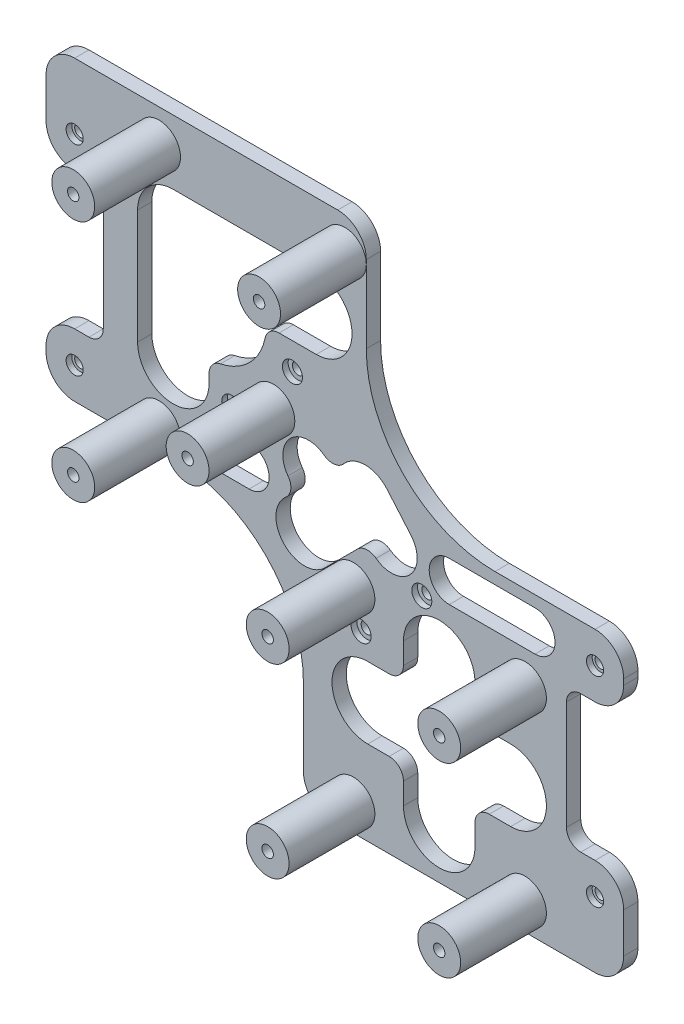
SolidWorks part; units mm, degrees
ref_plane "Přední rovina" through (0, 0, 0) normal (0, 0, 1) x (1, 0, 0)
ref_plane "Horní rovina" through (0, 0, 0) normal (0, 1, 0) x (1, 0, 0)
ref_plane "Pravá rovina" through (0, 0, 0) normal (1, 0, 0) x (0, 0, -1)
sketch "Skica1" plane through (0, 0, 0) normal (0, 0, 1) x (1, 0, 0)
  line L0 (0, 0) -> (101, 0) construction
  line L1 (0, 0) -> (0, 101) construction
  line L2 (-101, 101) -> (101, 101)
  line L3 (101, 101) -> (101, -101)
  line L4 (-101, 101) -> (-101, -101)
  line L5 (-101, -101) -> (101, -101)
  point P8 (-101, 0)
  dimension "D1" = 202
  dimension "D2" = 202
extrude "Přidat vysunutím1" add sketch "Skica1" along normal blind 5
sketch "Skica2" plane through (0, 0, 5) normal (0, 0, 1) x (1, 0, 0)
  line L0 (101, -101) -> (101, 101) construction
  line L1 (101, 101) -> (-101, 101) construction
  line L2 (11, 56) -> (11, 101)
  line L3 (56, 11) -> (101, 11)
  line L4 (11, 101) -> (101, 101)
  line L5 (101, 101) -> (101, 11)
  line L6 (0, 0) -> (-101, 101) construction
  line L7 (-56, -11) -> (-101, -11)
  line L8 (-101, -11) -> (-101, -101)
  line L9 (-101, -101) -> (-11, -101)
  line L10 (-11, -56) -> (-11, -101)
  arc A0 (11, 56) -> (56, 11) centre (56, 56) ccw
  arc A1 (-56, -11) -> (-11, -56) centre (-56, -56) cw
  dimension "D1" = 90
extrude "Odebrat vysunutím1" cut sketch "Skica2" against normal blind 10
sketch "Skica3" plane through (0, 0, 5) normal (0, 0, 1) x (1, 0, 0)
  line L0 (0, 0) -> (91, 0) construction
  line L1 (0, 0) -> (0, 101) construction
  line L2 (11, 101) -> (-101, 101) construction
  circle A2 centre (91, 0) radius 2
  circle A3 centre (-91, 0) radius 2
  circle A4 centre (91, -70) radius 2
  circle A5 centre (-91, 70) radius 2
  dimension "D4" = 70
  dimension "D5" = 2
  dimension "D3" = 4
  dimension "D1" = 2
  dimension "D2" = 91
  dimension "D6" = 70
extrude "Odebrat vysunutím2" cut sketch "Skica3" against normal through all
sketch "Skica4" plane through (0, 0, 5) normal (0, 0, 1) x (1, 0, 0)
  line L0 (0, 0) -> (0, 101) construction
  line L1 (11, 101) -> (-101, 101) construction
  circle A0 centre (91, 0) radius 3
  circle A1 centre (-91, 0) radius 3
  circle A2 centre (91, -70) radius 3
  circle A3 centre (-91, 70) radius 3
  dimension "D1" = 6
  dimension "D2" = 2
  dimension "D3" = 70
  dimension "D4" = 2
extrude "Odebrat vysunutím3" cut sketch "Skica4" against normal blind 2
sketch "Skica6" plane through (0, 0, 5) normal (0, 0, 1) x (1, 0, 0)
  line L0 (-56, -11) -> (-101, -11) construction
  line L5 (-69, -11) -> (11, -11) construction
  line L6 (-69, -11) -> (-69, 89) construction
  line L7 (-69, 89) -> (11, 89) construction
  line L8 (11, -11) -> (11, 89) construction
  line L9 (11, 101) -> (11, 56) construction
  line L10 (-11, -101) -> (-11, -56) construction
  line L11 (74, -91) -> (-1, -91) construction
  line L12 (74, -91) -> (74, -11) construction
  line L13 (74, -11) -> (-1, -11) construction
  line L14 (-1, -91) -> (-1, -11) construction
  line L15 (-11, -101) -> (101, -101) construction
  line L16 (-29, -11) -> (-29, 89) construction
  line L17 (-69, 89) -> (-54, 89) construction
  line L18 (-69, 89) -> (-69, 74) construction
  line L19 (-69, 74) -> (-54, 74) construction
  line L20 (-54, 89) -> (-54, 74) construction
  line L25 (11, 74) -> (-4, 74) construction
  line L26 (-4, 89) -> (-4, 74) construction
  line L27 (11, 89) -> (-4, 89) construction
  line L28 (11, 89) -> (11, 74) construction
  line L29 (-69, 39) -> (11, 39) construction
  line L34 (-69, 4) -> (-54, 4) construction
  line L35 (-54, -11) -> (-54, 4) construction
  line L36 (-69, -11) -> (-54, -11) construction
  line L37 (-69, -11) -> (-69, 4) construction
  line L38 (36.5, -91) -> (36.5, -11) construction
  line L39 (-1, -11) -> (14, -11) construction
  line L40 (-1, -11) -> (-1, -26) construction
  line L41 (-1, -26) -> (14, -26) construction
  line L42 (14, -11) -> (14, -26) construction
  line L43 (-1, -51) -> (74, -51) construction
  line L44 (74, -26) -> (59, -26) construction
  line L45 (59, -11) -> (59, -26) construction
  line L46 (74, -11) -> (59, -11) construction
  line L47 (74, -11) -> (74, -26) construction
  line L48 (74, -91) -> (59, -91) construction
  line L49 (59, -91) -> (59, -76) construction
  line L50 (74, -76) -> (59, -76) construction
  line L51 (74, -91) -> (74, -76) construction
  line L52 (-1, -76) -> (14, -76) construction
  line L53 (14, -91) -> (14, -76) construction
  line L54 (-1, -91) -> (14, -91) construction
  line L55 (-1, -91) -> (-1, -76) construction
  line L56 (-61.5, 89) -> (-61.5, 81.5) construction
  line L57 (-29, 29) -> (-14, 29) construction
  line L58 (-29, 29) -> (-29, 14) construction
  line L59 (-29, 14) -> (-14, 14) construction
  line L60 (-14, 29) -> (-14, 14) construction
  line L61 (-69, 81.5) -> (-61.5, 81.5) construction
  line L62 (-69, -3.5) -> (-61.5, -3.5) construction
  line L63 (-61.5, -3.5) -> (-61.5, 4) construction
  line L64 (3.5, 89) -> (3.5, 81.5) construction
  line L65 (3.5, 81.5) -> (11, 81.5) construction
  line L66 (-21.5, 14) -> (-21.5, 29) construction
  line L67 (-29, 21.5) -> (-14, 21.5) construction
  line L68 (6.5, -11) -> (6.5, -26) construction
  line L69 (-1, -18.5) -> (14, -18.5) construction
  line L70 (6.5, -91) -> (6.5, -76) construction
  line L71 (6.5, -83.5) -> (-1, -83.5) construction
  circle A0 centre (-61.5, 81.5) radius 7.5
  circle A1 centre (-61.5, -3.5) radius 7.5
  circle A2 centre (3.5, 81.5) radius 7.5
  circle A3 centre (-21.5, 21.5) radius 7.5
  circle A4 centre (6.5, -18.5) radius 7.5
  circle A5 centre (6.5, -83.5) radius 7.5
  circle A6 centre (66.5, -18.5) radius 7.5
  circle A7 centre (66.5, -83.5) radius 7.5
  dimension "D1" = 80
  dimension "D2" = 100
  dimension "D3" = 80
  dimension "D4" = 75
  dimension "D5" = 10
  dimension "D6" = 10
  dimension "D7" = 15
  dimension "D8" = 15
  dimension "D9" = 15
  dimension "D10" = 15
  dimension "D11" = 15
  dimension "D12" = 15
  dimension "D13" = 25
  dimension "D14" = 25
extrude "Přidat vysunutím2" add sketch "Skica6" along normal blind 30
sketch "Skica7" plane through (0, 0, 35) normal (0, 0, 1) x (1, 0, 0)
  circle A0 centre (-21.5, 21.5) radius 2
  circle A2 centre (-61.5, 81.5) radius 2
  circle A3 centre (3.5, 81.5) radius 2
  circle A4 centre (-61.5, -3.5) radius 2
  circle A5 centre (6.5, -18.5) radius 2
  circle A6 centre (66.5, -18.5) radius 2
  circle A7 centre (6.5, -83.5) radius 2
  circle A8 centre (66.5, -83.5) radius 2
  circle A12 centre (-61.5, 81.5) radius 7.5 construction
  circle A13 centre (6.5, -83.5) radius 7.5 construction
  circle A14 centre (66.5, -83.5) radius 7.5 construction
  circle A15 centre (66.5, -18.5) radius 7.5 construction
  circle A16 centre (6.5, -18.5) radius 7.5 construction
  circle A17 centre (-61.5, -3.5) radius 7.5 construction
  circle A18 centre (-21.5, 21.5) radius 7.5 construction
  circle A19 centre (3.5, 81.5) radius 7.5 construction
  dimension "D1" = 4
  dimension "D2" = 4
  dimension "D3" = 4
  dimension "D4" = 4
  dimension "D5" = 4
  dimension "D6" = 4
  dimension "D7" = 4
  dimension "D8" = 4
extrude "Odebrat vysunutím4" cut sketch "Skica7" against normal through all
sketch "Skica9" plane through (0, 0, 5) normal (0, 0, 1) x (1, 0, 0)
  line L0 (0, 0) -> (-25.4558, 25.4558) construction
  line L1 (0, 0) -> (0, 56.5264) construction
  line L2 (-2.8284, 2.8284) -> (11.7471, 17.404) construction
  line L3 (-25.4558, 25.4558) -> (-14.8492, 36.0624) construction
  circle A2 centre (-14.8492, 36.0624) radius 3.5
  circle A3 centre (-36.0624, 14.8492) radius 3.5
  circle A4 centre (30.4056, -9.1924) radius 3.5
  circle A5 centre (9.1924, -30.4056) radius 3.5
  dimension "D6" = 7
  dimension "D7" = 30
  dimension "D1" = 45
  dimension "D2" = 4
  dimension "D3" = 270
  dimension "D4" = 15
  dimension "D5" = 36
extrude "Odebrat vysunutím6" cut sketch "Skica9" against normal blind 2
sketch "Skica11" plane through (0, 0, 5) normal (0, 0, 1) x (1, 0, 0)
  circle A0 centre (-36.0624, 14.8492) radius 2
  circle A1 centre (-14.8492, 36.0624) radius 2
  circle A2 centre (30.4056, -9.1924) radius 2
  circle A3 centre (9.1924, -30.4056) radius 2
  dimension "D1" = 4
  dimension "D2" = 4
  dimension "D3" = 4
  dimension "D4" = 4
extrude "Odebrat vysunutím7" cut sketch "Skica11" against normal through all
sketch "Skica13" plane through (0, 0, 5) normal (0, 0, 1) x (1, 0, 0)
  line L0 (6.5, -11) -> (66.5, -11) construction
  line L1 (36.5, -11) -> (36.5, -26) construction
  line L2 (36.5, -26) -> (36.5, -51) construction
  line L3 (-1, -18.5) -> (-1, -83.5) construction
  line L4 (-1, -51) -> (36.5, -51) construction
  line L5 (11.5, -38.5) -> (24, -38.5)
  line L6 (24, -38.5) -> (24, -26)
  line L7 (24, -63.5) -> (24, -76)
  line L8 (11.5, -63.5) -> (24, -63.5)
  line L9 (49, -63.5) -> (49, -76)
  line L10 (61.5, -63.5) -> (49, -63.5)
  line L11 (49, -38.5) -> (49, -26)
  line L12 (61.5, -38.5) -> (49, -38.5)
  line L13 (11, 101) -> (11, 81.5) construction
  line L14 (-101, 101) -> (11, 101)
  line L15 (-101, 101) -> (-101, 93)
  line L16 (-101, 93) -> (11, 93)
  line L17 (11, 101) -> (11, 93)
  line L18 (101, -101) -> (101, 11) construction
  line L19 (-11, -101) -> (101, -101)
  line L20 (-11, -101) -> (-11, -93)
  line L21 (-11, -93) -> (101, -93)
  line L22 (101, -101) -> (101, -93)
  line L23 (-13.3605, 0) -> (-42, 0) construction
  line L24 (101, -59) -> (81, -59)
  line L25 (101, -59) -> (101, -11)
  line L26 (101, -11) -> (81, -11)
  line L27 (81, -59) -> (81, -11)
  line L28 (0, 0) -> (40, 0) construction
  line L29 (0, 0) -> (10.6066, 10.6066) construction
  line L30 (0, 0) -> (-9.1924, 9.1924) construction
  line L31 (-3.5355, -17.6777) -> (11.3137, -2.8284)
  line L32 (-16.8583, -2.8017) -> (-13.3605, 0)
  line L33 (-13.3605, 0) -> (-16.2168, 3.5658)
  line L34 (0, 0) -> (-13.3605, 0) construction
  line L35 (2.8017, 16.8583) -> (0, 13.3605)
  line L36 (0, 13.3605) -> (-3.5658, 16.2168)
  line L37 (10.6066, 10.6066) -> (19.799, 1.4142) construction
  line L38 (18.2006, 17.1128) -> (26.6336, 7.2698)
  line L39 (13.435, -4.9497) -> (11.3137, -2.8284)
  line L40 (0, 0) -> (0, 9.1924) construction
  line L41 (40, 0) -> (70, 0) construction
  line L42 (70, 7) -> (40, 7)
  line L43 (70, -7) -> (40, -7)
  line L44 (-42, -7) -> (-30, -7)
  line L45 (-42, 7) -> (-30, 7)
  circle A0 centre (6.5, -18.5) radius 7.5 construction
  circle A1 centre (6.5, -18.5) radius 7.5 construction
  circle A2 centre (66.5, -18.5) radius 7.5 construction
  circle A3 centre (66.5, -18.5) radius 7.5 construction
  arc A4 (49, -26) -> (24, -26) centre (36.5, -26) ccw
  circle A5 centre (6.5, -83.5) radius 7.5 construction
  circle A6 centre (6.5, -83.5) radius 7.5 construction
  arc A10 (11.5, -38.5) -> (11.5, -63.5) centre (11.5, -51) ccw
  arc A11 (61.5, -38.5) -> (61.5, -63.5) centre (61.5, -51) cw
  arc A12 (49, -76) -> (24, -76) centre (36.5, -76) cw
  arc A13 (-42, 7) -> (-42, -7) centre (-42, 0) ccw
  arc A14 (-30, -7) -> (-30, 7) centre (-30, 0) ccw
  circle A15 centre (91, 0) radius 2 construction
  circle A16 centre (91, -70) radius 2 construction
  arc A17 (18.2006, 17.1128) -> (2.8017, 16.8583) centre (10.6066, 10.6066) ccw
  arc A18 (-3.5355, -17.6777) -> (-16.8583, -2.8017) centre (-10.6066, -10.6066) cw
  arc A19 (-3.5658, 16.2168) -> (-16.2168, 3.5658) centre (-9.1924, 9.1924) ccw
  arc A20 (13.435, -4.9497) -> (26.6336, 7.2698) centre (19.799, 1.4142) ccw
  arc A21 (40, 7) -> (40, -7) centre (40, 0) ccw
  arc A22 (70, -7) -> (70, 7) centre (70, 0) ccw
  point P30 (36.5, -51)
  point P90 (-30, 7)
  dimension "D1" = 25
  dimension "D3" = 25
  dimension "D5" = 8
  dimension "D4" = 25
  dimension "D7" = 11
  dimension "D8" = 11
  dimension "D13" = 20
  dimension "D14" = 18
  dimension "D16" = 90
  dimension "D17" = 18
  dimension "D18" = 13
  dimension "D19" = 14
  dimension "D20" = 14
  dimension "D23" = 12
  dimension "D25" = 14
  dimension "D26" = 14
  dimension "D2" = 25
  dimension "D6" = 8
  dimension "D9" = 20
  dimension "D10" = 45
  dimension "D11" = 90
  dimension "D12" = 15
  dimension "D15" = 13
  dimension "D21" = 30
  dimension "D22" = 40
  dimension "D24" = 30
extrude "Odebrat vysunutím8" cut sketch "Skica13" against normal through all
sketch "Skica14" plane through (0, 0, 5) normal (0, 0, 1) x (1, 0, 0)
  line L0 (-101, 93) -> (-101, -11) construction
  line L1 (-101, 59) -> (-81, 59)
  line L2 (-101, 59) -> (-101, 11)
  line L3 (-101, 11) -> (-81, 11)
  line L4 (-81, 59) -> (-81, 11)
  line L5 (-6.5, 58) -> (-56.5, 58) construction
  line L6 (11, 81.5) -> (11, 56) construction
  line L7 (-101, 93) -> (11, 93) construction
  line L8 (-56.5, 58) -> (-56.5, 18) construction
  line L9 (-56.5, 38) -> (-37.1316, 38) construction
  line L10 (-69, 58) -> (-69, 18)
  line L11 (-44, 18) -> (-44, 45.5) construction
  line L12 (-6.5, 45.5) -> (-44, 45.5) construction
  line L13 (-56.5, 70.5) -> (-6.5, 70.5)
  line L14 (-6.5, 45.5) -> (-24, 45.5)
  line L15 (-44, 18) -> (-44, 25.5)
  circle A0 centre (-91, 70) radius 2 construction
  circle A1 centre (-91, 0) radius 2 construction
  arc A2 (-6.5, 45.5) -> (-6.5, 70.5) centre (-6.5, 58) ccw
  arc A3 (-56.5, 70.5) -> (-69, 58) centre (-56.5, 58) ccw
  arc A4 (-44, 18) -> (-69, 18) centre (-56.5, 18) cw
  arc A5 (-44, 25.5) -> (-24, 45.5) centre (-44, 45.5) ccw
  dimension "D2" = 11
  dimension "D4" = 25
  dimension "D5" = 25
  dimension "D10" = 40
  dimension "D1" = 11
  dimension "D3" = 20
  dimension "D6" = 50
  dimension "D7" = 17.5
  dimension "D8" = 35
  dimension "D9" = 40
extrude "Odebrat vysunutím9" cut sketch "Skica14" against normal through all
fillet "Zaoblit1" radius 5 13 edges at (49, -38.5, 2.5) (24, -38.5, 2.5) (49, -63.5, 2.5) (24, -63.5, 2.5) (81, -59, 2.5) (81, -11, 2.5) (-24, 45.5, 2.5) (-44, 25.5, 2.5) (-81, 59, 2.5) (-81, 11, 2.5) (11.3137, -2.8284, 2.5) (-13.3605, 0, 2.5) (0, 13.3605, 2.5)
fillet "Zaoblit2" radius 10 10 edges at (-101, 93, 2.5) (-101, -11, 2.5) (-11, -93, 2.5) (101, -93, 2.5) (101, 11, 2.5) (11, 93, 2.5) (101, -59, 2.5) (101, -11, 2.5) (-101, 59, 2.5) (-101, 11, 2.5)
